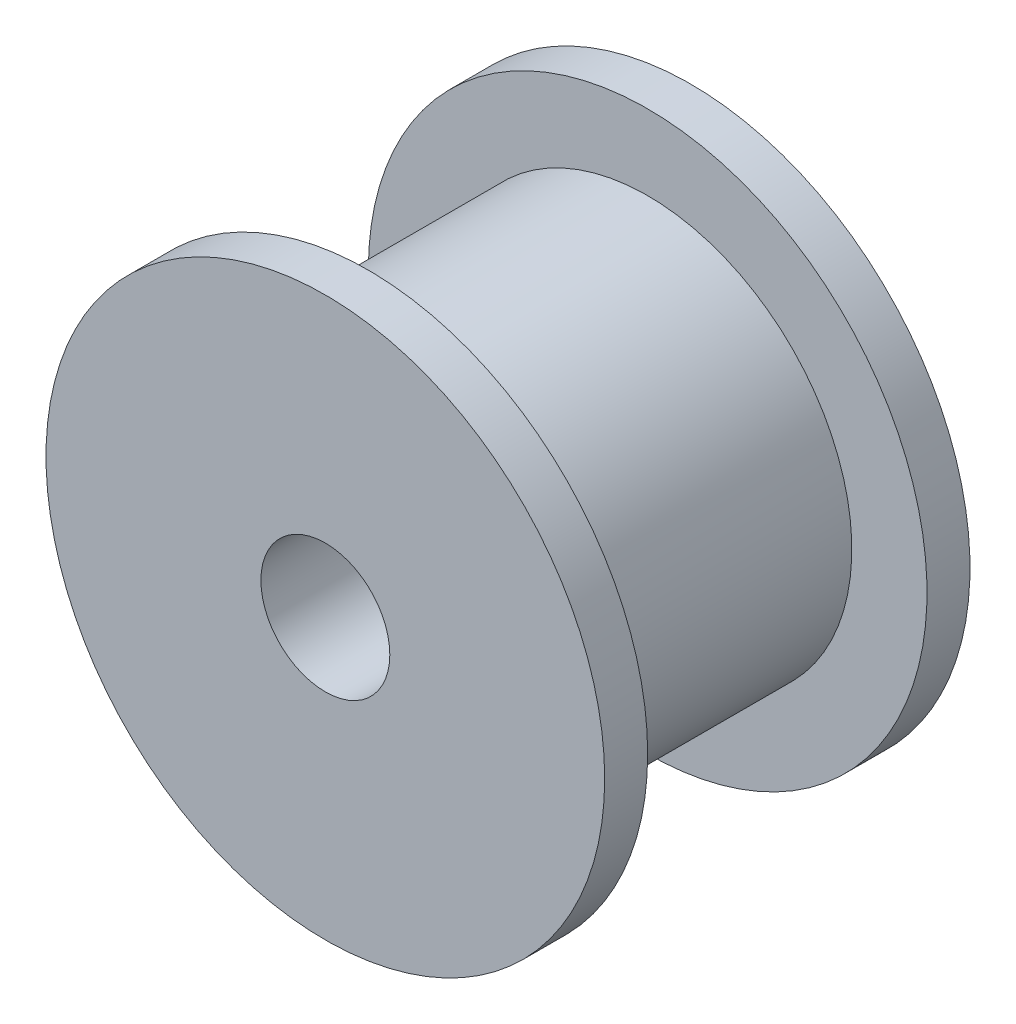
SolidWorks part; units mm, degrees
ref_plane "前视基准面" through (0, 0, 0) normal (0, 0, 1) x (1, 0, 0)
ref_plane "上视基准面" through (0, 0, 0) normal (0, 1, 0) x (1, 0, 0)
ref_plane "右视基准面" through (0, 0, 0) normal (1, 0, 0) x (0, 0, -1)
sketch "草图1" plane through (0, 0, 0) normal (0, 0, 1) x (1, 0, 0)
  circle A0 centre (0, 0) radius 4.75
extrude "凸台-拉伸1" add sketch "草图1" along normal blind 8.5
sketch "草图2" plane through (0, 0, 8.5) normal (0, 0, 1) x (1, 0, 0)
  circle A0 centre (0, 0) radius 6.5
extrude "凸台-拉伸2" add sketch "草图2" against normal blind 1
sketch "草图3" plane through (0, 0, 0) normal (0, 0, -1) x (-1, 0, 0)
  circle A0 centre (0, 0) radius 6.5
extrude "凸台-拉伸3" add sketch "草图3" against normal blind 1
sketch "草图4" plane through (0, 0, 0) normal (0, 0, -1) x (-1, 0, 0)
  circle A0 centre (0, 0) radius 1.5
extrude "切除-拉伸1" cut sketch "草图4" against normal blind 12
